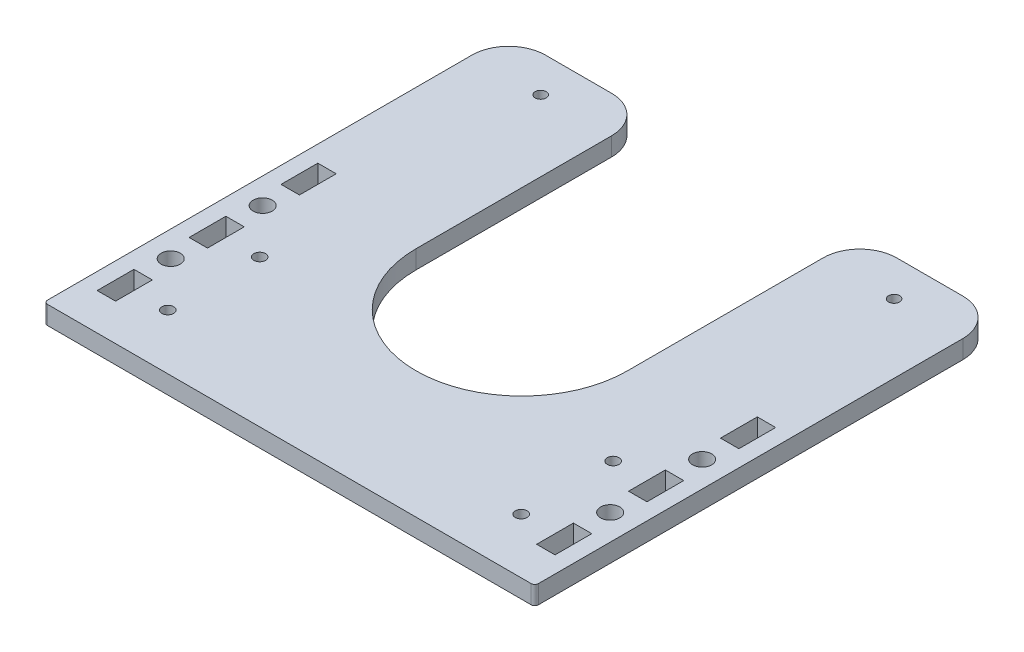
SolidWorks part; units mm, degrees
material "6061 Alloy"
ref_plane "Front Plane" through (0, 0, 0) normal (0, 0, 1) x (1, 0, 0)
ref_plane "Top Plane" through (0, 0, 0) normal (0, 1, 0) x (1, 0, 0)
ref_plane "Right Plane" through (0, 0, 0) normal (1, 0, 0) x (0, 0, -1)
sketch "Sketch1" plane through (0, 0, 0) normal (0, 1, 0) x (1, 0, 0)
  line L0 (-66.75, 63.2) -> (66.75, 63.2)
  line L1 (66.75, 63.2) -> (66.75, -63.2)
  line L2 (-66.75, -63.2) -> (66.75, -63.2)
  line L3 (-66.75, 63.2) -> (-66.75, -63.2)
  line L4 (-52.75, -49.2) -> (-66.75, -49.2) construction
  line L5 (-59.75, -53.2) -> (-59.75, -18.2) construction
  line L6 (0, 49.2) -> (0, -49.2) construction
  line L7 (-62.25, -43.2) -> (-57.25, -43.2)
  line L8 (-62.25, -43.2) -> (-62.25, -53.2)
  line L9 (-62.25, -53.2) -> (-57.25, -53.2)
  line L10 (-57.25, -43.2) -> (-57.25, -53.2)
  line L11 (-52.75, 49.2) -> (52.75, 49.2) construction
  line L12 (-52.75, 49.2) -> (-52.75, -49.2) construction
  line L13 (-52.75, -49.2) -> (52.75, -49.2) construction
  line L14 (52.75, 49.2) -> (52.75, -49.2) construction
  line L15 (-52.75, 49.2) -> (52.75, -49.2) construction
  line L16 (-52.75, -49.2) -> (52.75, 49.2) construction
  line L17 (-62.25, -28.2) -> (-57.25, -28.2)
  line L18 (-62.25, -28.2) -> (-62.25, -18.2)
  line L19 (-62.25, -18.2) -> (-57.25, -18.2)
  line L20 (-57.25, -28.2) -> (-57.25, -18.2)
  line L21 (62.25, -18.2) -> (57.25, -18.2)
  line L22 (57.25, -28.2) -> (57.25, -18.2)
  line L23 (62.25, -28.2) -> (62.25, -18.2)
  line L24 (62.25, -28.2) -> (57.25, -28.2)
  line L25 (57.25, -43.2) -> (57.25, -53.2)
  line L26 (62.25, -43.2) -> (57.25, -43.2)
  line L27 (62.25, -43.2) -> (62.25, -53.2)
  line L28 (62.25, -53.2) -> (57.25, -53.2)
  line L29 (-54.8606, -10.7) -> (-66.75, -10.7) construction
  line L30 (-57.25, 1.8) -> (-62.25, 1.8) construction
  line L31 (-57.25, 6.8) -> (-57.25, -3.2)
  line L32 (-62.25, -3.2) -> (-57.25, -3.2)
  line L33 (-62.25, 6.8) -> (-62.25, -3.2)
  line L34 (-57.25, -23.2) -> (-62.25, -23.2) construction
  line L35 (-62.25, 6.8) -> (-57.25, 6.8)
  line L36 (57.25, 1.8) -> (62.25, 1.8) construction
  line L37 (62.25, 6.8) -> (57.25, 6.8)
  line L38 (62.25, 6.8) -> (62.25, -3.2)
  line L39 (62.25, -3.2) -> (57.25, -3.2)
  line L40 (57.25, 6.8) -> (57.25, -3.2)
  circle A0 centre (-59.75, -35.7) radius 2.6
  circle A1 centre (59.75, -35.7) radius 2.6
  circle A2 centre (-48.05, -48.2) radius 1.6
  circle A3 centre (48.05, -48.2) radius 1.6
  circle A4 centre (-59.75, -10.7) radius 2.6
  circle A5 centre (59.75, -10.7) radius 2.6
  point P0 (0, 0)
  point P10 (0, 0)
  point P36 (-59.75, -49.2)
  dimension "D8" = 5.2
  dimension "D9" = 3.2
  dimension "D1" = 98.4
  dimension "D2" = 14
  dimension "D3" = 5
  dimension "D4" = 10
  dimension "D5" = 105.5
  dimension "D6" = 10
  dimension "D7" = 35
extrude "Boss-Extrude1" add sketch "Sketch1" along normal blind 5
sketch "Sketch2" plane through (0, 5, 0) normal (0, 1, 0) x (1, 0, 0)
  line L0 (-28.75, 86.6787) -> (-28.75, 0)
  line L1 (-28.75, 86.6787) -> (28.75, 86.6787)
  line L2 (66.75, 63.2) -> (-66.75, 63.2) construction
  line L3 (0, 63.2) -> (0, 0) construction
  line L4 (28.75, 86.6787) -> (28.75, 0)
  arc A0 (-28.75, 0) -> (28.75, 0) centre (0, 0) ccw
  point P10 (0, 86.6787)
  dimension "D1" = 28.75
extrude "Cut-Extrude2" cut sketch "Sketch2" against normal blind 10 contours L0 A0 L4 L1
fillet "Fillet2" radius 10 4 edges at (66.75, 2.5, -63.2) (28.75, 2.5, -63.2) (-66.75, 2.5, -63.2) (-28.75, 2.5, -63.2)
sketch "Sketch5" plane through (0, 0, 0) normal (0, -1, 0) x (1, 0, 0)
  line L0 (0, 0) -> (0, 58.2) construction
  line L1 (-65.75, 58.2) -> (65.75, 58.2) construction
  circle A0 centre (48.05, 23.2) radius 1.6
  circle A2 centre (48.05, -53.2) radius 1.5
  circle A3 centre (48.05, -53.2) radius 1.5 construction
  circle A4 centre (-48.05, -53.2) radius 1.5
  circle A5 centre (-48.05, 23.2) radius 1.6
  dimension "D1" = 3.2
extrude "Cut-Extrude3" cut sketch "Sketch5" against normal up to next
fillet "Fillet3" radius 1 2 edges at (-66.75, 2.5, 63.2) (66.75, 2.5, 63.2)
ref_plane "Plane1" through (0, 0, 48.2) normal (0, 0, -1) x (-1, 0, 0)
ref_plane "Plane2" through (0, 0, 23.2) normal (0, 0, 1) x (1, 0, 0)
